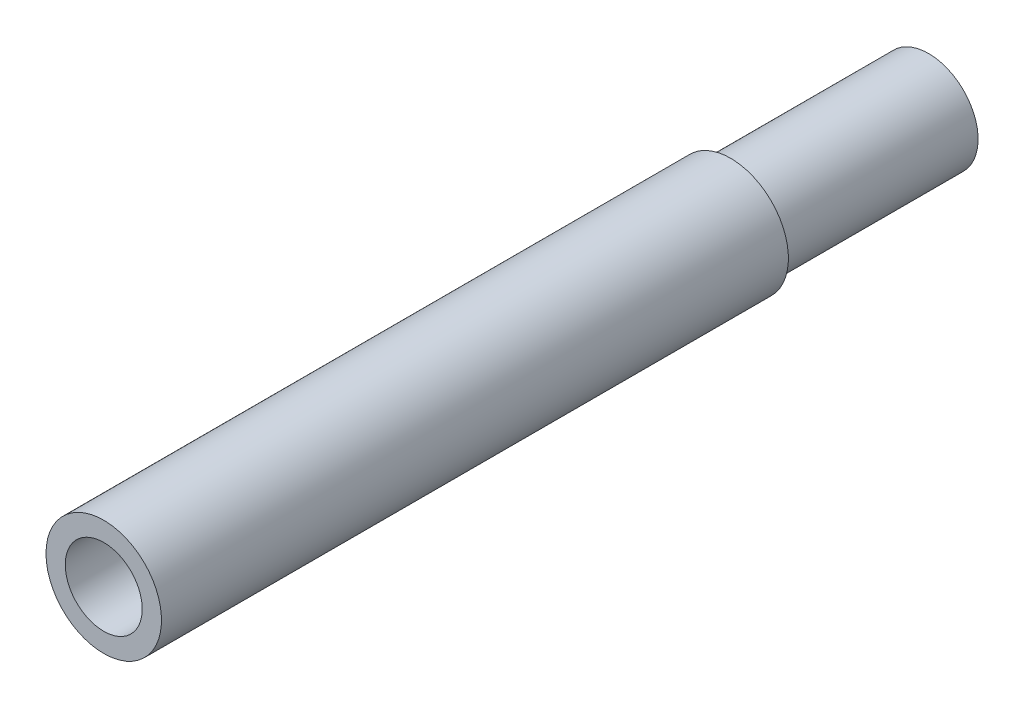
SolidWorks part; units mm, degrees
ref_plane "Front Plane" through (0, 0, 0) normal (0, 0, 1) x (1, 0, 0)
ref_plane "Top Plane" through (0, 0, 0) normal (0, 1, 0) x (1, 0, 0)
ref_plane "Right Plane" through (0, 0, 0) normal (1, 0, 0) x (0, 0, -1)
sketch "Sketch2" plane through (0, 0, 0) normal (0, 0, 1) x (1, 0, 0)
  circle A0 centre (0, 0) radius 7
  circle A1 centre (0, 0) radius 10.5
  dimension "D1" = 14
  dimension "D2" = 21
extrude "Boss-Extrude1" add sketch "Sketch2" along normal blind 114
sketch "Sketch4" plane through (0, 0, 0) normal (0, 0, -1) x (-1, 0, 0)
  circle A0 centre (0, 0) radius 7
  circle A1 centre (0, 0) radius 9
  dimension "D1" = 14
  dimension "D2" = 18
extrude "Boss-Extrude2" add sketch "Sketch4" along normal blind 36
fillet "Fillet2" [suppressed] radius 1
fillet "Fillet3" [suppressed] radius 1.75
